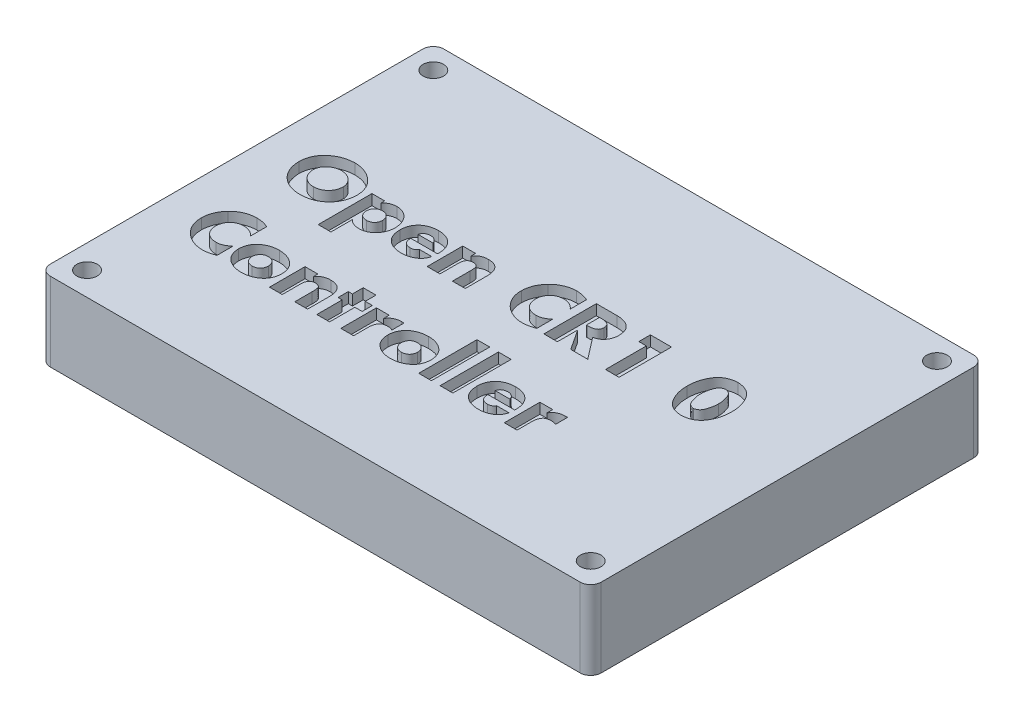
SolidWorks part; units mm, degrees
ref_plane "Front" through (0, 0, 0) normal (0, 0, 1) x (1, 0, 0)
ref_plane "Top" through (0, 0, 0) normal (0, 1, 0) x (1, 0, 0)
ref_plane "Right" through (0, 0, 0) normal (1, 0, 0) x (0, 0, -1)
sketch "Sketch1" plane through (0, 0, 0) normal (0, 1, 0) x (1, 0, 0)
  line L1 (-52.5, 37.5) -> (52.5, 37.5)
  line L2 (-52.5, 37.5) -> (-52.5, -37.5)
  line L3 (-52.5, -37.5) -> (52.5, -37.5)
  line L4 (52.5, 37.5) -> (52.5, -37.5)
  line L5 (-52.5, 37.5) -> (52.5, -37.5) construction
  line L6 (-52.5, -37.5) -> (52.5, 37.5) construction
  point P0 (0, 0)
  dimension "D1" = 105
  dimension "D2" = 75
extrude "Boss-Extrude1" add sketch "Sketch1" along normal blind 15
hole_wizard "M3.5 Clearance Hole1" positions "Sketch3" profile "Sketch4" hole size "M3.5" standard "ANSI Metric" end condition through all
sketch "Sketch3" plane through (0, 15, 0) normal (0, 1, 0) x (1, 0, 0)
  line L1 (48, -33) -> (-48, -33)
  line L2 (48, -33) -> (48, 33)
  line L3 (48, 33) -> (-48, 33)
  line L4 (-48, -33) -> (-48, 33)
  line L5 (48, -33) -> (-48, 33) construction
  line L6 (48, 33) -> (-48, -33) construction
  point P0 (48, 33)
  point P2 (-48, 33)
  point P4 (-48, -33)
  point P6 (48, -33)
  point P42 (-48, -33)
  point P43 (48, -33)
  point P44 (48, 33)
  point P45 (0, 0)
  dimension "D1" = 96
  dimension "D2" = 66
sketch "Sketch4" plane through (48, 15, -33) normal (1, 0, 0) x (0, 0, 1)
  line L0 (0, 0) -> (0, 15)
  line L1 (0, 15) -> (1.95, 15)
  line L2 (1.95, 15) -> (1.95, 0)
  line L5 (1.95, 0) -> (0, 0)
  line L11 (0, -6.35) -> (0, 107.95) construction
  dimension "Thru Hole Dia." = 3.9
  dimension "Thru Hole Depth" = 15
sketch "Sketch5" plane through (0, 15, 0) normal (0, 1, 0) x (1, 0, 0)
  line L0 (-46.1206, 0) -> (46.1206, 0) construction
  text T0 "<b>Open CR1.0 </b>\r\n<b>Controller</b>" font "Futura Book" height 10
  point P3 (0, 0)
  point P5 (46.1206, 0)
extrude "Cut-Extrude1" cut sketch "Sketch5" against normal blind 2
fillet "Fillet37" radius 2 4 edges at (52.5, 7.5, 37.5) (-52.5, 7.5, -37.5) (52.5, 7.5, -37.5) (-52.5, 7.5, 37.5)
